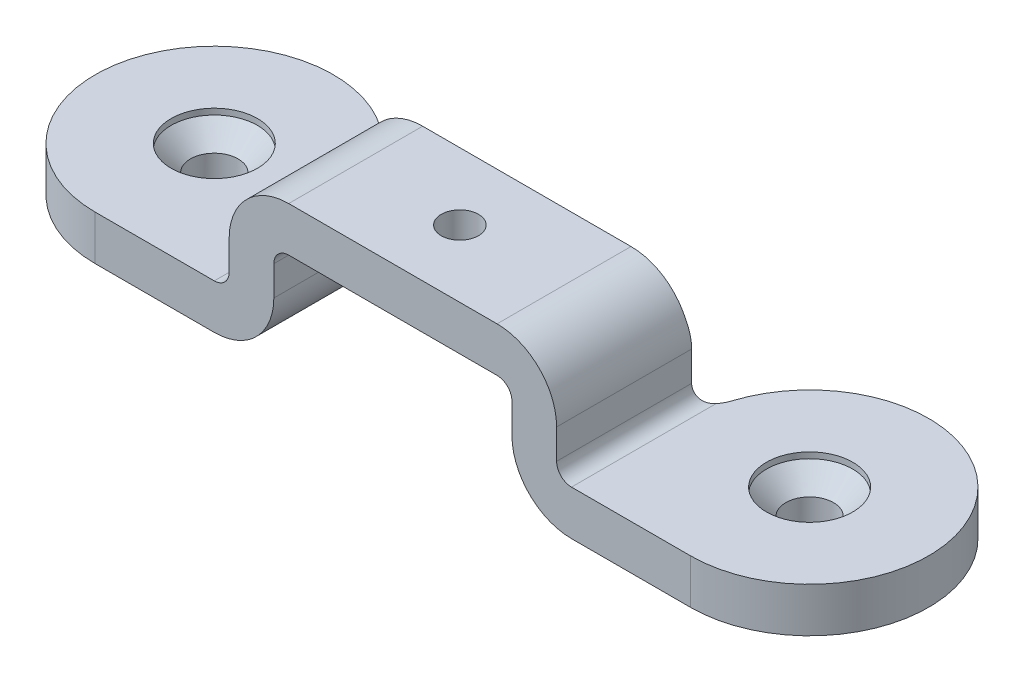
SolidWorks part; units mm, degrees
material "PET"
ref_plane "Plan de face" through (0, 0, 0) normal (0, 0, 1) x (1, 0, 0)
ref_plane "Plan de dessus" through (0, 0, 0) normal (0, 1, 0) x (1, 0, 0)
ref_plane "Plan de droite" through (0, 0, 0) normal (1, 0, 0) x (0, 0, -1)
sketch "Esquisse1" plane through (0, 0, 0) normal (0, 1, 0) x (1, 0, 0)
  line L0 (0, -8.5421) -> (0, 4.0935) construction
  line L1 (-20, -8) -> (20, -8)
  line L3 (10.4606, 1) -> (-10.4606, 1)
  arc A0 (-12.3685, 2.4) -> (-20, -8) centre (-20, 0) ccw
  arc A1 (-10.4606, 1) -> (-12.3685, 2.4) centre (-10.4606, 3) cw
  arc A2 (10.4606, 1) -> (12.3685, 2.4) centre (10.4606, 3) ccw
  arc A3 (12.3685, 2.4) -> (20, -8) centre (20, 0) cw
  circle A4 centre (20, 0) radius 8 construction
  point P10 (-29.5859, 0)
  dimension "D1" = 2
  dimension "D2" = 40
  dimension "D3" = 9
extrude "Boss.-Extru.1" add sketch "Esquisse1" along normal blind 10
sketch "Esquisse2" plane through (0, 0, 0) normal (0, 0, 1) x (1, 0, 0)
  line L0 (0, 13.1144) -> (0, -2.8486) construction
  line L1 (7, 10) -> (-7, 10)
  line L2 (-20, 10) -> (20, 10) construction
  line L3 (-11, 6) -> (-11, 4)
  line L4 (-12, 3) -> (-28, 3)
  line L5 (-28, 10) -> (-28, 0) construction
  line L6 (-28, 3) -> (-28, 0)
  line L7 (-28, 0) -> (-12, 0)
  line L8 (-20, 0) -> (20, 0) construction
  line L9 (-8, 4) -> (-8, 6)
  line L10 (-7, 7) -> (7, 7)
  line L11 (28, 0) -> (12, 0)
  line L12 (28, 3) -> (28, 0)
  line L13 (12, 3) -> (28, 3)
  line L14 (11, 6) -> (11, 4)
  line L15 (8, 4) -> (8, 6)
  arc A0 (-12, 0) -> (-8, 4) centre (-12, 4) ccw
  arc A1 (-7, 10) -> (-11, 6) centre (-7, 6) ccw
  arc A2 (-8, 6) -> (-7, 7) centre (-7, 6) cw
  arc A3 (-11, 4) -> (-12, 3) centre (-12, 4) cw
  arc A4 (11, 4) -> (12, 3) centre (12, 4) ccw
  arc A5 (12, 0) -> (8, 4) centre (12, 4) cw
  arc A6 (8, 6) -> (7, 7) centre (7, 6) ccw
  arc A7 (7, 10) -> (11, 6) centre (7, 6) cw
  point P20 (-8, 0)
  point P23 (-11, 10)
  point P39 (0, 7)
  point P40 (0, 10)
  dimension "D1" = 4
  dimension "D2" = 1
  dimension "D3" = 3
  dimension "D4" = 3
  dimension "D5" = 3
  dimension "D6" = 22
extrude "Enlèv. mat.-Extru.1" cut sketch "Esquisse2" against normal through all and the other way through all flip side to cut
sketch "Esquisse3" plane through (0, 0, 0) normal (0, -1, 0) x (1, 0, 0)
  circle A0 centre (20, 0) radius 4
extrude "Boss.-Extru.2" add sketch "Esquisse3" along normal blind 0.3
hole_wizard "Fraisage pour vis à tête fraisée à 6 pans creux M31" positions "Esquisse5" profile "Esquisse4" countersink size "M3" standard "ISO" end condition up to next
sketch "Esquisse5" plane through (0, 3, 0) normal (0, 1, 0) x (1, 0, 0)
  point P0 (20, 0)
sketch "Esquisse4" plane through (20, 3, 0) normal (1, 0, 0) x (0, 0, 1)
  line L0 (0, 0) -> (0, 3.3)
  line L1 (0, 3.3) -> (1.6, 3.3)
  line L2 (1.6, 3.3) -> (1.6, 1.7)
  line L3 (1.6, 1.7) -> (2.9, 0.4)
  line L4 (2.9, 0.4) -> (2.9, 0)
  line L6 (2.9, 0) -> (0, 0)
  line L7 (-1.6, 1.7) -> (-2.9, 0.4) construction
  line L11 (0, -6.35) -> (0, 107.95) construction
  dimension "Diamètre du perçage jusqu'au prochain" = 3.2
  dimension "Profondeur du perçage jusqu'au prochain" = 3.3
  dimension "Diamètre du fraisage" = 5.8
  dimension "Angle du fraisage" = 90
  dimension "Dégagement de la tête" = 0.4
hole_wizard "Trou taraudé M31" positions "Esquisse7" profile "Esquisse6" tap size "M3" standard "ISO" end condition up to next
sketch "Esquisse7" plane through (0, 10, 0) normal (0, 1, 0) x (1, 0, 0)
  point P0 (0, -3.5)
sketch "Esquisse6" plane through (0, 10, 3.5) normal (1, 0, 0) x (0, 0, 1)
  line L0 (0, 0) -> (0, 3)
  line L1 (0, 3) -> (1.25, 3)
  line L2 (1.25, 3) -> (1.25, 0)
  line L5 (1.25, 0) -> (0, 0)
  line L11 (0, -6.35) -> (0, 107.95) construction
  dimension "Diamètre du trou pour taraudage jusqu'au prochain" = 2.5
  dimension "Profondeur du trou pour taraudage jusqu'au prochain" = 3
cosmetic thread "Filetage de perçage1" parameters "D2"=3
mirror "Symétrie1" about plane through (0, 0, 0) normal (1, 0, 0) of "Fraisage pour vis à tête fraisée à 6 pans creux M31", "Boss.-Extru.2"
